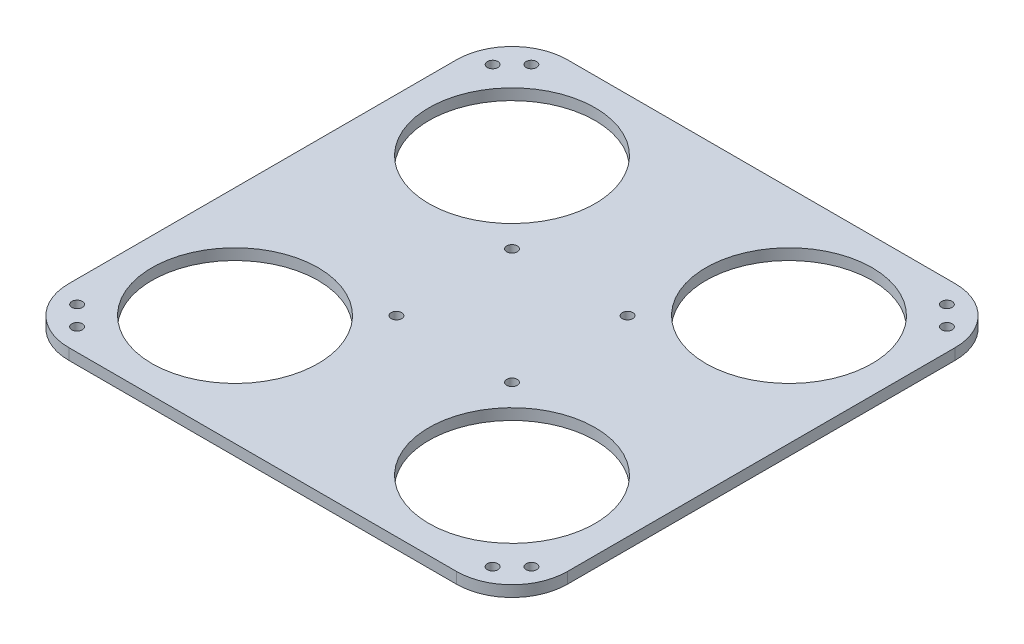
SolidWorks part; units mm, degrees
ref_plane "Спереди" through (0, 0, 0) normal (0, 0, 1) x (1, 0, 0)
ref_plane "Сверху" through (0, 0, 0) normal (0, 1, 0) x (1, 0, 0)
ref_plane "Справа" through (0, 0, 0) normal (1, 0, 0) x (0, 0, -1)
sketch "Эскиз1" plane through (0, 0, 0) normal (0, 1, 0) x (1, 0, 0)
  line L0 (-75, -82) -> (75, -82) construction
  line L1 (-90, -90) -> (90, -90)
  line L2 (-90, -90) -> (-90, 90)
  line L3 (-90, 90) -> (90, 90)
  line L4 (90, -90) -> (90, 90)
  line L5 (0, 90) -> (0, -90) construction
  line L6 (-90, 0) -> (90, 0) construction
  line L7 (-82, -75) -> (82, -75) construction
  line L8 (-82, -75) -> (-82, 75) construction
  line L9 (-82, 75) -> (82, 75) construction
  line L10 (82, -75) -> (82, 75) construction
  line L11 (0, 75) -> (0, -75) construction
  line L12 (-82, 0) -> (82, 0) construction
  line L13 (-75, -82) -> (75, -82) construction
  line L14 (-75, -82) -> (-75, 82) construction
  line L15 (-75, 82) -> (75, 82) construction
  line L16 (75, -82) -> (75, 82) construction
  line L17 (0, 82) -> (0, -82) construction
  line L18 (-75, 0) -> (75, 0) construction
  line L19 (-82, -75) -> (82, -75) construction
  line L20 (0, 0) -> (62.0453, 62.0453) construction
  circle A0 centre (-75, 82) radius 1.9
  circle A1 centre (-82, 75) radius 1.9
  circle A2 centre (82, 75) radius 1.9
  circle A3 centre (75, 82) radius 1.9
  circle A4 centre (75, -82) radius 1.9
  circle A5 centre (82, -75) radius 1.9
  circle A6 centre (-82, -75) radius 1.9
  circle A7 centre (-75, -82) radius 1.9
  circle A8 centre (20.8597, 20.8597) radius 1.9
  circle A9 centre (20.8597, -20.8597) radius 1.9
  circle A10 centre (-20.8597, -20.8597) radius 1.9
  circle A11 centre (-20.8597, 20.8597) radius 1.9
  circle A12 centre (-50, 50) radius 30
  circle A13 centre (50, 50) radius 30
  circle A14 centre (-50, -50) radius 30
  circle A15 centre (50, -50) radius 30
  point P0 (0, 0)
  point P4 (0, 0)
  point P8 (0, 0)
  point P26 (-48.425, 48.0481)
  point P33 (0, 0)
  dimension "D5" = 3.8
  dimension "D9" = 60
  dimension "D1" = 164
  dimension "D2" = 150
  dimension "D3" = 180
  dimension "D4" = 180
  dimension "D6" = 45
  dimension "D7" = 29.5
  dimension "D8" = 4
extrude "Бобышка-Вытянуть1" add sketch "Эскиз1" along normal blind 4
fillet "Скругление1" radius 20 4 edges at (-90, 2, 90) (-90, 2, -90) (90, 2, -90) (90, 2, 90)
